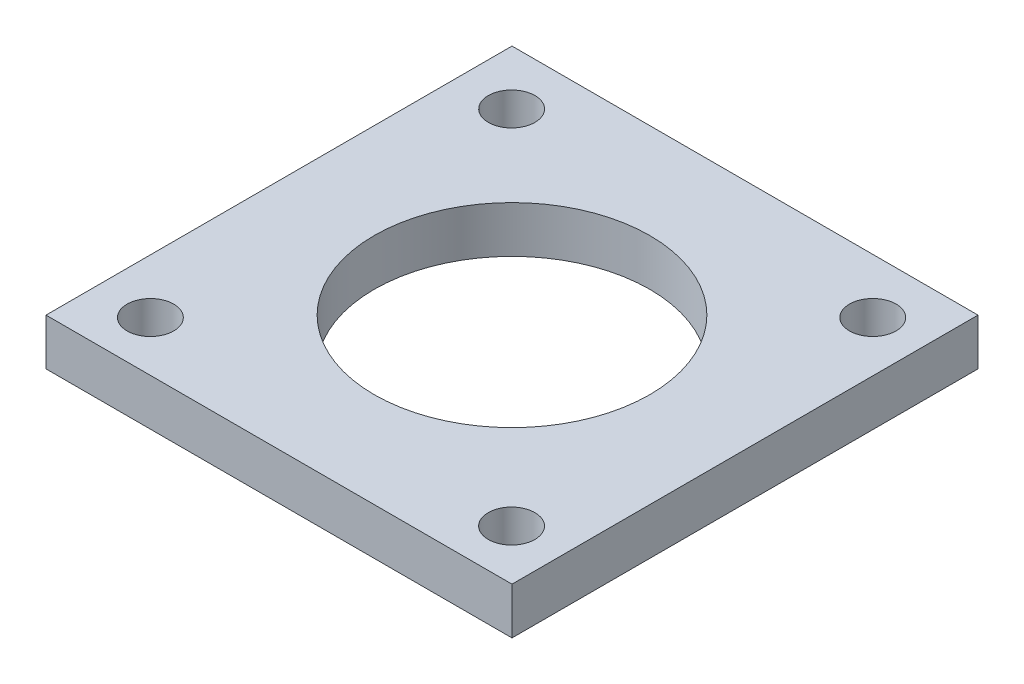
SolidWorks part; units mm, degrees
ref_plane "Front Plane" through (0, 0, 0) normal (0, 0, 1) x (1, 0, 0)
ref_plane "Top Plane" through (0, 0, 0) normal (0, 1, 0) x (1, 0, 0)
ref_plane "Right Plane" through (0, 0, 0) normal (1, 0, 0) x (0, 0, -1)
sketch "Sketch1" plane through (0, 0, 0) normal (0, 1, 0) x (1, 0, 0)
  line L0 (-20.0551, -19.0528) -> (19.9449, -19.0528)
  line L1 (-20.0551, -19.0528) -> (-20.0551, 20.9472)
  line L2 (-20.0551, 20.9472) -> (19.9449, 20.9472)
  line L3 (19.9449, -19.0528) -> (19.9449, 20.9472)
  line L4 (-20.0551, -19.0528) -> (19.9449, 20.9472) construction
  line L5 (-20.0551, 20.9472) -> (19.9449, -19.0528) construction
  circle A0 centre (-0.0551, 0.9472) radius 11.8292
  circle A1 centre (-15.3933, 16.2546) radius 2
  circle A2 centre (15.6067, 16.2546) radius 2
  circle A3 centre (-15.3933, -14.7528) radius 2
  circle A4 centre (15.6077, -14.7529) radius 2
  dimension "D1" = 23.6584
  dimension "D2" = 4
  dimension "D8" = 15.3381
  dimension "D3" = 20
  dimension "D4" = 20
  dimension "D5" = 15.6619
  dimension "D6" = 15.3074
  dimension "D7" = 15.3074
  dimension "D9" = 15.7
  dimension "D10" = 15.3381
  dimension "D11" = 15.7001
  dimension "D12" = 15.6628
extrude "Boss-Extrude1" add sketch "Sketch1" along normal blind 4
